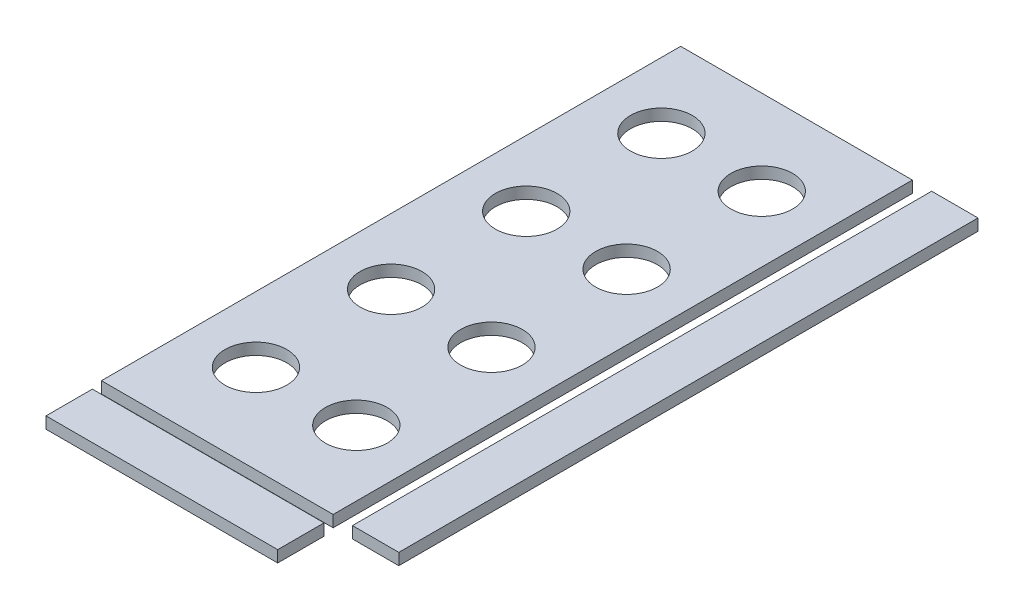
SolidWorks part; units mm, degrees
ref_plane "Front Plane" through (0, 0, 0) normal (0, 0, 1) x (1, 0, 0)
ref_plane "Top Plane" through (0, 0, 0) normal (0, 1, 0) x (1, 0, 0)
ref_plane "Right Plane" through (0, 0, 0) normal (1, 0, 0) x (0, 0, -1)
sketch "Sketch1" plane through (0, 0, 0) normal (0, 1, 0) x (1, 0, 0)
  line L1 (-38.3775, 137.6443) -> (21.6225, 137.6443)
  line L2 (-38.3775, 137.6443) -> (-38.3775, -12.3557)
  line L3 (-38.3775, -12.3557) -> (21.6225, -12.3557)
  line L4 (21.6225, 137.6443) -> (21.6225, -12.3557)
  dimension "D1" = 60
  dimension "D2" = 150
extrude "Boss-Extrude2" add sketch "Sketch1" along normal blind 3
sketch "Sketch2" plane through (0, 0, 0) normal (0, 1, 0) x (1, 0, 0)
  line L0 (21.6225, -12.3557) -> (21.6225, 137.6443) construction
  line L1 (26.6225, 137.6443) -> (38.6225, 137.6443)
  line L2 (26.6225, 137.6443) -> (26.6225, -12.3557)
  line L3 (26.6225, -12.3557) -> (38.6225, -12.3557)
  line L4 (38.6225, 137.6443) -> (38.6225, -12.3557)
  line L5 (-38.3775, -12.3557) -> (21.6225, -12.3557) construction
  dimension "D1" = 12
  dimension "D2" = 150
  dimension "D3" = 5
  dimension "D4" = 0
extrude "Boss-Extrude4" add sketch "Sketch2" along normal blind 3 separate body
sketch "Sketch3" plane through (0, 0, 0) normal (0, 1, 0) x (1, 0, 0)
  line L1 (43.6225, 47.6443) -> (55.6225, 47.6443)
  line L2 (43.6225, 47.6443) -> (43.6225, -12.3557)
  line L3 (43.6225, -12.3557) -> (55.6225, -12.3557)
  line L4 (55.6225, 47.6443) -> (55.6225, -12.3557)
  line L5 (38.6225, -12.3557) -> (38.6225, 137.6443) construction
  line L6 (26.6225, -12.3557) -> (38.6225, -12.3557) construction
  dimension "D1" = 12
  dimension "D2" = 60
  dimension "D3" = 5
  dimension "D4" = 0
extrude "Boss-Extrude5" add sketch "Sketch3" along normal blind 3 separate body
sketch "Sketch4" plane through (0, 3, 0) normal (0, 1, 0) x (1, 0, 0)
  line L0 (-38.3775, -12.3557) -> (21.6225, -12.3557) construction
  line L1 (21.6225, -12.3557) -> (21.6225, 137.6443) construction
  line L2 (-38.3775, 137.6443) -> (-38.3775, -12.3557) construction
  circle A0 centre (4.6225, 10.6443) radius 8
  circle A1 centre (-21.3775, 10.6443) radius 8
  circle A2 centre (4.6225, 45.6443) radius 8
  circle A3 centre (-21.3775, 45.6443) radius 8
  circle A4 centre (4.6225, 80.6443) radius 8
  circle A5 centre (-21.3775, 80.6443) radius 8
  circle A6 centre (4.6225, 115.6443) radius 8
  circle A7 centre (-21.3775, 115.6443) radius 8
  dimension "D1" = 16
  dimension "D2" = 23
  dimension "D3" = 17
  dimension "D4" = 16
  dimension "D5" = 26
  dimension "D6" = 17
  dimension "D7" = 4
extrude "Cut-Extrude1" cut sketch "Sketch4" against normal blind 3
move or copy body "Body-Move/Copy1" bodies to move or copy 106 copy no rotation origin (99.6296, 0, -43.2668) rotation axis (0, 1, 0) rotation angle 90
move or copy body "Body-Move/Copy2" bodies to move or copy 108 copy no translate (-132.9222, 0, 14.6886)
